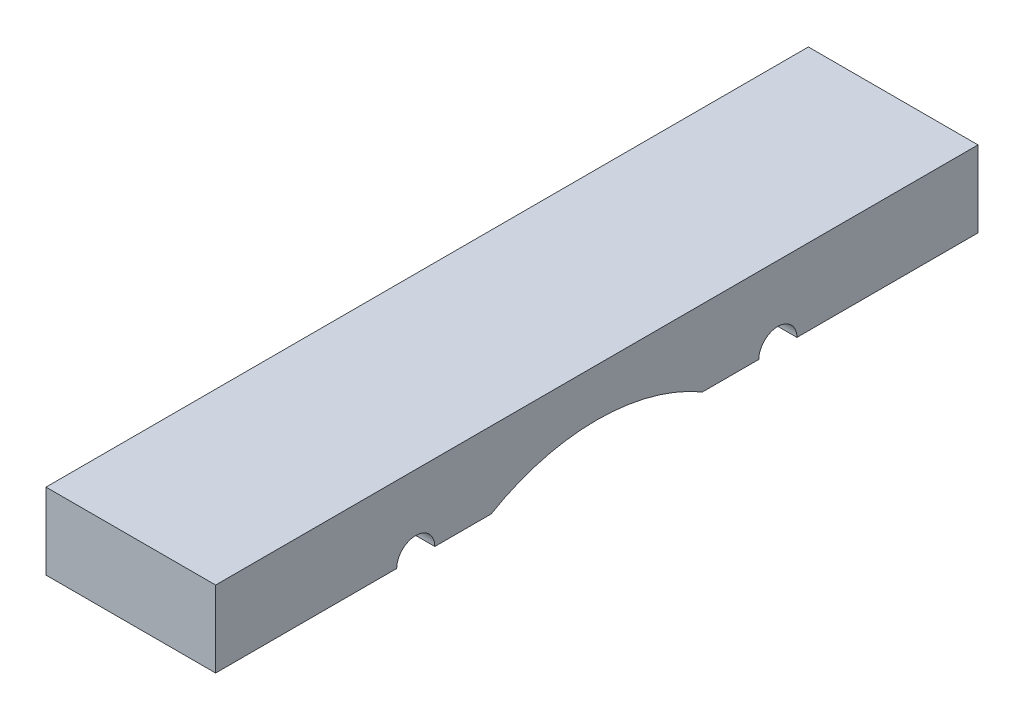
SolidWorks part; units mm, degrees
ref_plane "Front Plane" through (0, 0, 0) normal (0, 0, 1) x (1, 0, 0)
ref_plane "Top Plane" through (0, 0, 0) normal (0, 1, 0) x (1, 0, 0)
ref_plane "Right Plane" through (0, 0, 0) normal (1, 0, 0) x (0, 0, -1)
sketch "Sketch1" plane through (0, 0, 0) normal (0, 1, 0) x (1, 0, 0)
  line L1 (-4.45, -20) -> (4.45, -20)
  line L2 (-4.45, -20) -> (-4.45, 20)
  line L3 (-4.45, 20) -> (4.45, 20)
  line L4 (4.45, -20) -> (4.45, 20)
  line L5 (-4.45, -20) -> (4.45, 20) construction
  line L6 (-4.45, 20) -> (4.45, -20) construction
  point P0 (0, 0)
  dimension "D1" = 8.9
  dimension "D2" = 40
extrude "Boss-Extrude1" add sketch "Sketch1" along normal blind 29.39
sketch "Sketch5" plane through (-4.45, 0, 0) normal (-1, 0, 0) x (0, 0, 1)
  line L0 (0, 29.39) -> (0, 0) construction
  line L1 (-20, 29.39) -> (20, 29.39) construction
  line L2 (-20, 0) -> (20, 0) construction
  line L3 (-13.95, 23.3) -> (13.95, 23.3)
  line L4 (-13.95, 23.3) -> (-13.95, 0)
  line L5 (-13.95, 0) -> (13.95, 0)
  line L6 (13.95, 23.3) -> (13.95, 0)
  line L7 (-13.95, 23.3) -> (13.95, 0) construction
  line L8 (-13.95, 0) -> (13.95, 23.3) construction
  point P5 (0, 11.65)
  dimension "D1" = 27.9
  dimension "D2" = 23.3
extrude "Cut-Extrude2" cut sketch "Sketch5" against normal through all contours L4 L3 L6 L5
sketch "Sketch7" plane through (4.45, 0, 0) normal (1, 0, 0) x (0, 0, -1)
  line L0 (13.95, 23.3) -> (-13.95, 23.3) construction
  line L1 (0, 29.39) -> (0, 23.3) construction
  line L2 (-20, 29.39) -> (20, 29.39) construction
  circle A0 centre (9.5, 23.3) radius 1
  circle A1 centre (-9.5, 23.3) radius 1
  circle A2 centre (0, 13.8) radius 11
  point P10 (0, 13.8)
  dimension "D1" = 9.5
  dimension "D2" = 9.5
extrude "Cut-Extrude3" cut sketch "Sketch7" against normal through all
sketch "Sketch8" plane through (4.45, 0, 0) normal (1, 0, 0) x (0, 0, -1)
  line L0 (-20, 0) -> (20, 0) construction
  line L1 (-20, 0) -> (20, 0)
  line L2 (-20, 0) -> (-20, 23.3)
  line L3 (-20, 23.3) -> (20, 23.3)
  line L4 (20, 0) -> (20, 23.3)
  line L5 (20, 29.39) -> (20, 0) construction
  point P8 (0, 0)
extrude "Cut-Extrude4" cut sketch "Sketch8" against normal through all
sketch "Sketch9" plane through (4.45, 0, 0) normal (1, 0, 0) x (0, 0, -1)
  line L0 (20, 29.39) -> (20, 23.3) construction
  line L1 (-20, 29.39) -> (20, 29.39)
  line L2 (-20, 29.39) -> (-20, 27.3)
  line L3 (-20, 27.3) -> (20, 27.3)
  line L4 (20, 29.39) -> (20, 27.3)
  dimension "D1" = 2.09
extrude "Cut-Extrude5" cut sketch "Sketch9" against normal through all
